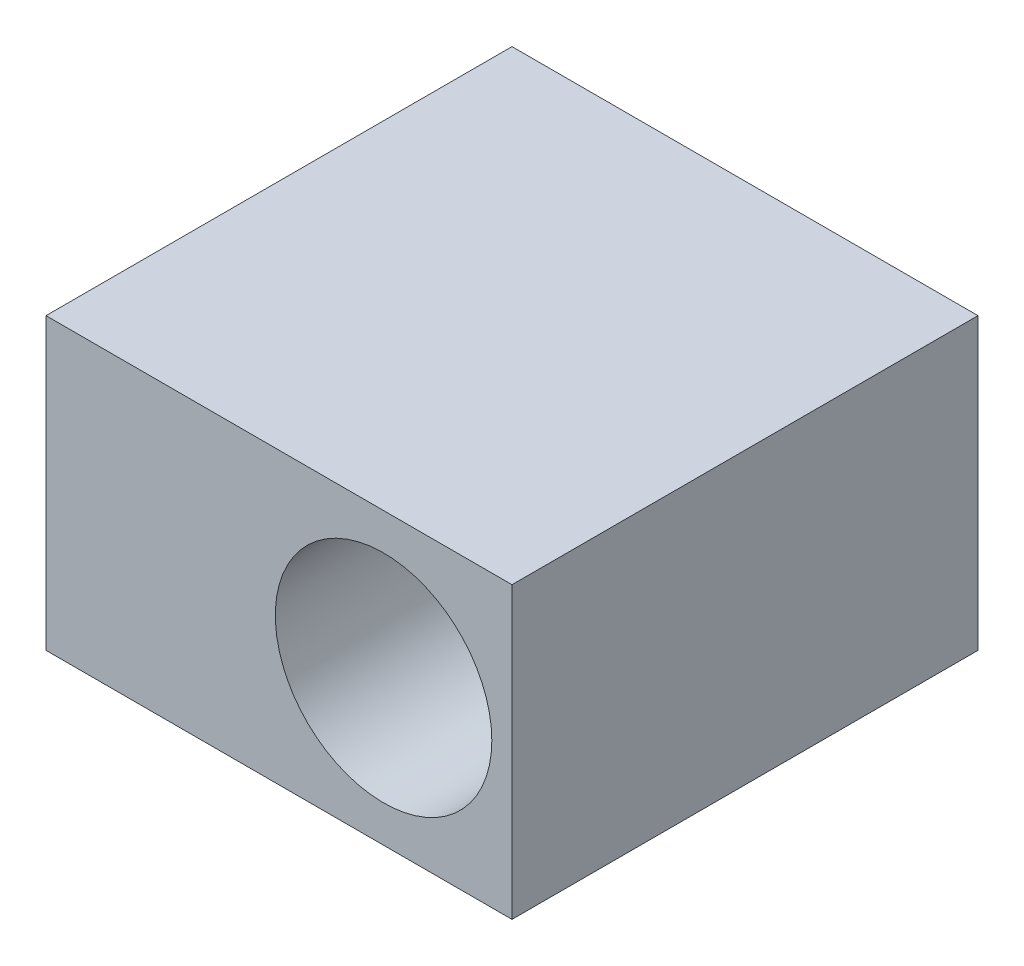
SolidWorks part; units mm, degrees
material "Brass"
ref_plane "Front" through (0, 0, 0) normal (0, 0, 1) x (1, 0, 0)
ref_plane "Top" through (0, 0, 0) normal (0, 1, 0) x (1, 0, 0)
ref_plane "Right" through (0, 0, 0) normal (1, 0, 0) x (0, 0, -1)
sketch "Sketch1" plane through (0, 0, 0) normal (0, 1, 0) x (1, 0, 0)
  line L1 (-6.35, -6.35) -> (6.35, -6.35)
  line L2 (-6.35, -6.35) -> (-6.35, 6.35)
  line L3 (-6.35, 6.35) -> (6.35, 6.35)
  line L4 (6.35, -6.35) -> (6.35, 6.35)
  line L5 (-6.35, -6.35) -> (6.35, 6.35) construction
  line L6 (-6.35, 6.35) -> (6.35, -6.35) construction
  point P0 (0, 0)
  dimension "D1" = 12.7
  dimension "D2" = 12.7
extrude "Boss-Extrude1" add sketch "Sketch1" along normal blind 7.9
sketch "Sketch2" plane through (0, 0, 6.35) normal (0, 0, 1) x (1, 0, 0)
  line L0 (6.35, 7.9) -> (6.35, 0) construction
  circle A0 centre (2.85, 3.95) radius 2.95
  dimension "D1" = 5.9
  dimension "D2" = 3.5
extrude "Cut-Extrude1" cut sketch "Sketch2" against normal through all
sketch "Sketch3" plane through (0, 0, 0) normal (0, -1, 0) x (1, 0, 0)
  line L0 (-6.35, -6.35) -> (-6.35, 6.35) construction
  circle A0 centre (-2.65, 0) radius 3.65
  dimension "D1" = 7.3
  dimension "D2" = 3.7
extrude "Boss-Extrude2" add sketch "Sketch3" along normal blind 3.1
chamfer "Chamfer1" distance 1.8 angle 59 1 edges at (-2.65, -3.1, -3.65)
sketch "Sketch4" plane through (-6.35, 0, 0) normal (-1, 0, 0) x (0, 0, 1)
  line L0 (-6.35, 7.9) -> (-6.35, 0) construction
  circle A0 centre (-5.225, 3.95) radius 1.05
  point P4 (-6.35, 3.95)
  dimension "D1" = 2.1
  dimension "D2" = 1.125
extrude "Cut-Extrude2" cut sketch "Sketch4" against normal blind 4
